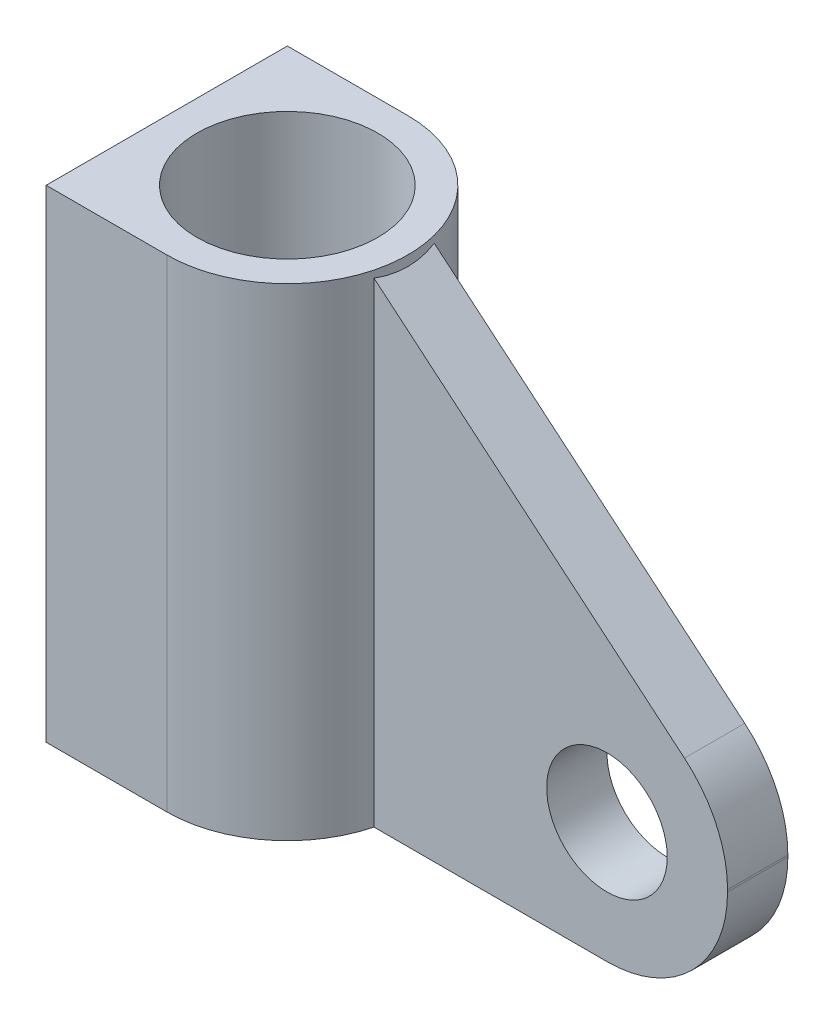
SolidWorks part; units mm, degrees
ref_plane "Front Plane" through (0, 0, 0) normal (0, 0, 1) x (1, 0, 0)
ref_plane "Top Plane" through (0, 0, 0) normal (0, 1, 0) x (1, 0, 0)
ref_plane "Right Plane" through (0, 0, 0) normal (1, 0, 0) x (0, 0, -1)
sketch "Sketch1" plane through (0, 0, 0) normal (0, 1, 0) x (1, 0, 0)
  circle A0 centre (0, 0) radius 6.35
  circle A1 centre (0, 0) radius 4.7625
  dimension "D1" = 12.7
  dimension "D2" = 9.525
extrude "Boss-Extrude1" add sketch "Sketch1" along normal mid plane 25.4
sketch "Sketch2" plane through (0, 0, 0) normal (0, 0, 1) x (1, 0, 0)
  line L0 (6.35, 12.7) -> (-6.35, 12.7) construction
  line L1 (5.715, -12.7) -> (18.415, -12.7)
  line L2 (5.715, 12.7) -> (5.715, -12.7)
  line L3 (24.765, -6.35) -> (24.765, -6.2459)
  line L4 (22.4967, -1.3815) -> (5.715, 12.7)
  line L5 (6.35, -12.7) -> (6.35, 12.7) construction
  line L6 (-6.35, -12.7) -> (6.35, -12.7) construction
  arc A0 (18.415, -12.7) -> (24.765, -6.35) centre (18.415, -6.35) ccw
  arc A1 (24.765, -6.2459) -> (22.4967, -1.3815) centre (18.415, -6.2459) ccw
  point P10 (24.765, -12.7)
  dimension "D3" = 6.35
  dimension "D4" = 6.35
  dimension "D1" = 19.05
  dimension "D2" = 0.635
  dimension "D5" = 50
extrude "Boss-Extrude2" add sketch "Sketch2" along normal mid plane 3.175
sketch "Sketch3" plane through (0, 0, 1.5875) normal (0, 0, 1) x (1, 0, 0)
  circle A0 centre (18.415, -6.35) radius 3.175
  dimension "D1" = 6.35
extrude "Cut-Extrude1" cut sketch "Sketch3" against normal through all
ref_plane "Plane1" through (-6.35, 0, 0) normal (-1, 0, 0) x (0, 0, 1)
sketch "Sketch4" plane through (-6.35, 0, 0) normal (-1, 0, 0) x (0, 0, 1)
  line L1 (-6.35, 12.7) -> (6.35, 12.7)
  line L2 (-6.35, 12.7) -> (-6.35, -12.7)
  line L3 (-6.35, -12.7) -> (6.35, -12.7)
  line L4 (6.35, 12.7) -> (6.35, -12.7)
extrude "Boss-Extrude3" add sketch "Sketch4" against normal up to next
